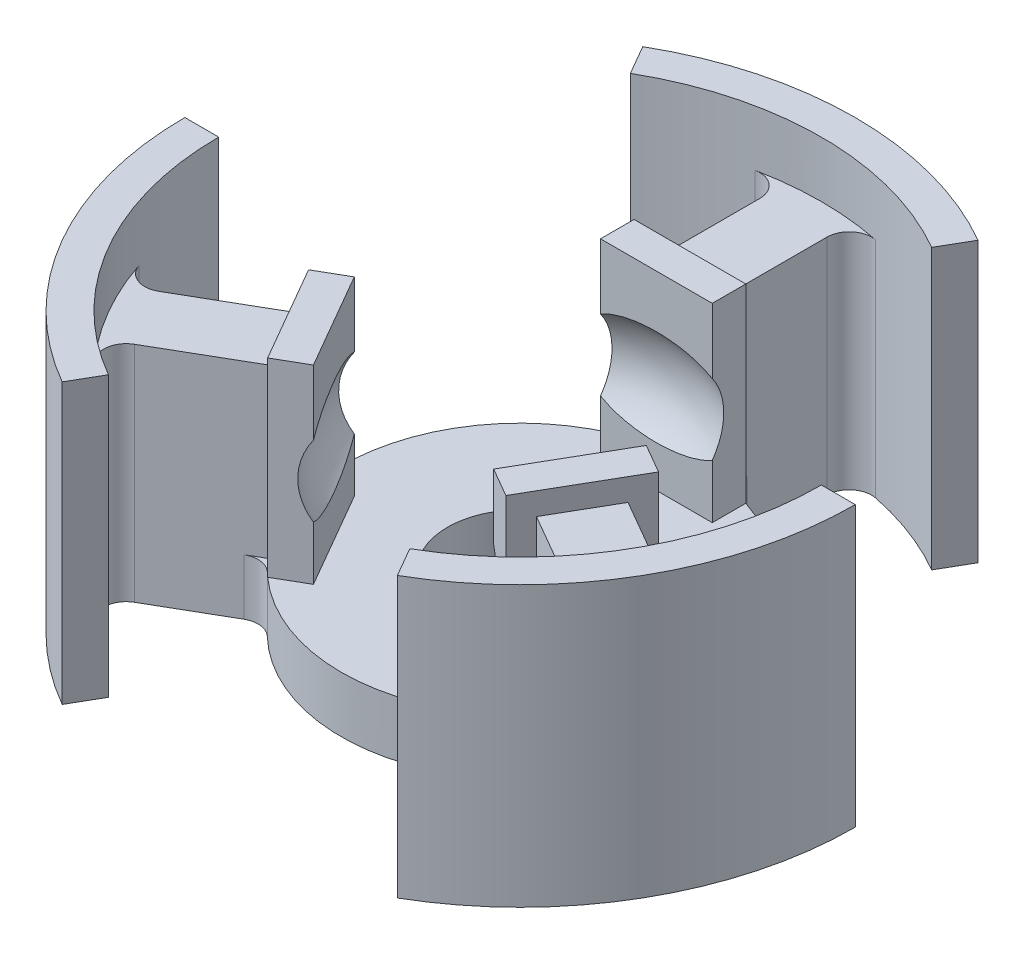
SolidWorks part; units mm, degrees
ref_plane "Front" through (0, 0, 0) normal (0, 0, 1) x (1, 0, 0)
ref_plane "Top" through (0, 0, 0) normal (0, 1, 0) x (1, 0, 0)
ref_plane "Right" through (0, 0, 0) normal (1, 0, 0) x (0, 0, -1)
sketch "草图1" plane through (0, 0, 0) normal (0, 1, 0) x (1, 0, 0)
  circle A2 centre (0, 0) radius 16
  circle A3 centre (0, 0) radius 6.5
extrude "凸台-拉伸1" add sketch "草图1" along normal blind 5
sketch "草图2" plane through (0, 0, 0) normal (0, 1, 0) x (1, 0, 0)
  line L0 (0, 17.4559) -> (0, -17.1438) construction
  line L2 (5, 12.1987) -> (-5, 12.1987)
  line L3 (5, 12.1987) -> (5, 15.1987)
  line L4 (5, 15.1987) -> (-5, 15.1987)
  line L5 (-5, 12.1987) -> (-5, 15.1987)
  line L6 (5, 12.1987) -> (-5, 15.1987) construction
  line L7 (5, 15.1987) -> (-5, 12.1987) construction
  circle A0 centre (0, 0) radius 16 construction
  point P4 (0, 13.6987)
  dimension "D1" = 10
  dimension "D2" = 3
extrude "凸台-拉伸2" add sketch "草图2" along normal blind 22
sketch "草图3" plane through (0, 0, 0) normal (0, 1, 0) x (1, 0, 0)
  line L0 (0, 0) -> (0, 25.8196) construction
  line L1 (-15, 25.9808) -> (-13.4841, 23.3552)
  line L2 (15, 25.9808) -> (13.4841, 23.3552)
  arc A0 (15, 25.9808) -> (-15, 25.9808) centre (0, 0) ccw
  arc A1 (13.4841, 23.3552) -> (-13.4841, 23.3552) centre (0, 0) ccw
extrude "凸台-拉伸3" add sketch "草图3" along normal blind 25 contours A1 L1 A0 L2
sketch "草图4" plane through (0, 0, 0) normal (0, 1, 0) x (1, 0, 0)
  line L2 (0, 30) -> (0, 10.5572) construction
  line L3 (3, 14.4029) -> (-3, 14.4029)
  line L4 (3, 14.4029) -> (3, 27.9909)
  line L5 (3, 27.9909) -> (-3, 27.9909)
  line L6 (-3, 14.4029) -> (-3, 27.9909)
  line L7 (3, 14.4029) -> (-3, 27.9909) construction
  line L8 (3, 27.9909) -> (-3, 14.4029) construction
  arc A1 (15, 25.9808) -> (-15, 25.9808) centre (0, 0) ccw construction
  point P0 (0, 21.1969)
  dimension "D1" = 6
extrude "凸台-拉伸4" add sketch "草图4" along normal blind 20 contours L6 L5 L4 L3
sketch "草图5" plane through (0, 0, 0) normal (1, 0, 0) x (0, 0, -1)
  line L0 (8.4, 0) -> (8.4, 17.7747)
  line L1 (-16, 0) -> (15.7162, 0) construction
  line L2 (8.4, 13) -> (-8.5516, 13)
  line L3 (12.1987, 22) -> (12.1987, 5) construction
  line L4 (0, -2.521) -> (0, 24.9573) construction
  line L5 (12.1987, 17.3032) -> (8.4, 13)
  line L6 (12.1987, 8.6968) -> (8.4, 13)
  arc A0 (12.1987, 17.3032) -> (12.1987, 8.6968) centre (8.4, 13) cw
  dimension "D1" = 8.4
  dimension "D2" = 13
revolve "切除-旋转1" cut sketch "草图5" angle 360 about L4
fillet "圆角1" radius 2 1 edges at (3, 10, -26.8008)
fillet "圆角2" radius 2 1 edges at (-3, 10, -26.8008)
fillet "圆角3" radius 2 1 edges at (-3, 2.5, -15.7162)
fillet "圆角4" radius 2 1 edges at (3, 2.5, -15.7162)
pattern_circular "阵列(圆周)4" count 3 every 120 about axis through (0, 0, 0) along (0, 1, 0) of "凸台-拉伸2", "凸台-拉伸4", "切除-旋转1"
pattern_circular "阵列(圆周)5" count 3 over 360 about axis through (0, 0, 0) along (0, 1, 0) of "凸台-拉伸3"
fillet "圆角5" radius 2 8 edges at (-21.7102, 10, 15.9985) (-12.1107, 2.5, 10.4562) (-15.1107, 2.5, 5.26) (-24.7102, 10, 10.8023) (15.1107, 2.5, 5.26) (24.7102, 10, 10.8023) (12.1107, 2.5, 10.4562) (21.7102, 10, 15.9985)
